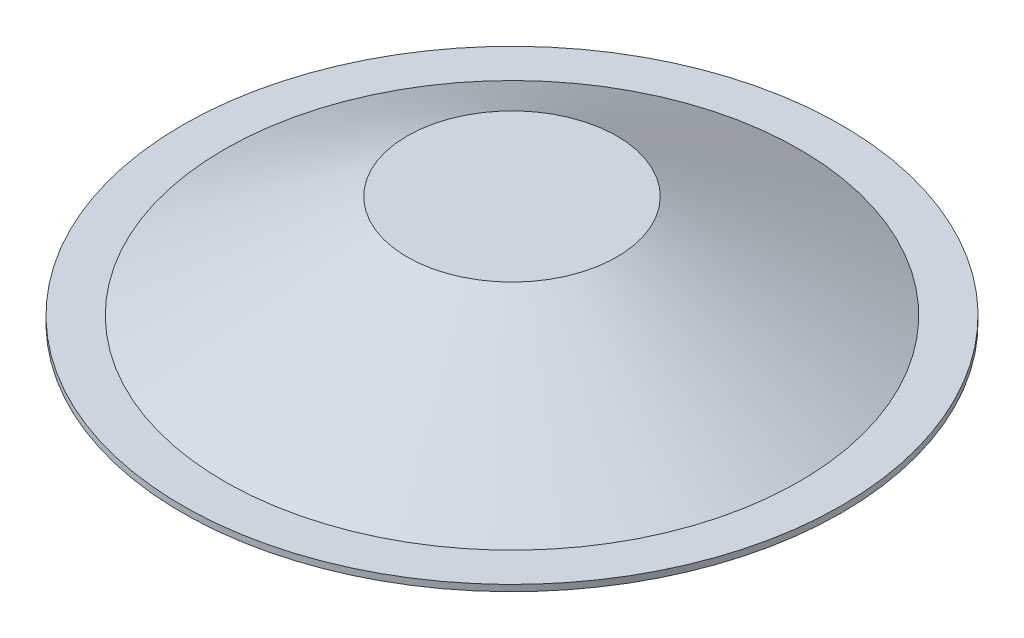
SolidWorks part; units mm, degrees
ref_plane "Front Plane" through (0, 0, 0) normal (0, 0, 1) x (1, 0, 0)
ref_plane "Top Plane" through (0, 0, 0) normal (0, 1, 0) x (1, 0, 0)
ref_plane "Right Plane" through (0, 0, 0) normal (1, 0, 0) x (0, 0, -1)
sketch "Sketch4" plane through (0, 0, 0) normal (0, 0, 1) x (1, 0, 0)
  line L0 (0, 0) -> (0, -3)
  line L1 (0, 0) -> (-50, 0)
  line L2 (-50, 0) -> (-137.1228, -49.0878)
  line L4 (-137.1228, -49.0878) -> (-157.1228, -49.0878)
  line L5 (-157.1228, -49.0878) -> (-157.1228, -52.0878)
  line L6 (-157.1228, -52.0878) -> (-136.3358, -52.0878)
  line L7 (0, -3) -> (-49.213, -3)
  line L8 (-49.213, -3) -> (-136.3358, -52.0878)
  point P8 (0, -49.0878)
  point P9 (0, 0)
  point P10 (0, 0)
  dimension "D1" = 50
  dimension "D2" = 100
  dimension "D3" = 3
  dimension "D4" = 20
  dimension "D5" = 3
  dimension "D6" = 3
  dimension "D7" = 136.3358
sketch "Sketch6" plane through (0, 0, 0) normal (0, 0, 1) x (1, 0, 0)
revolve "Revolve5" add sketch "Sketch4" angle 360 about L0
